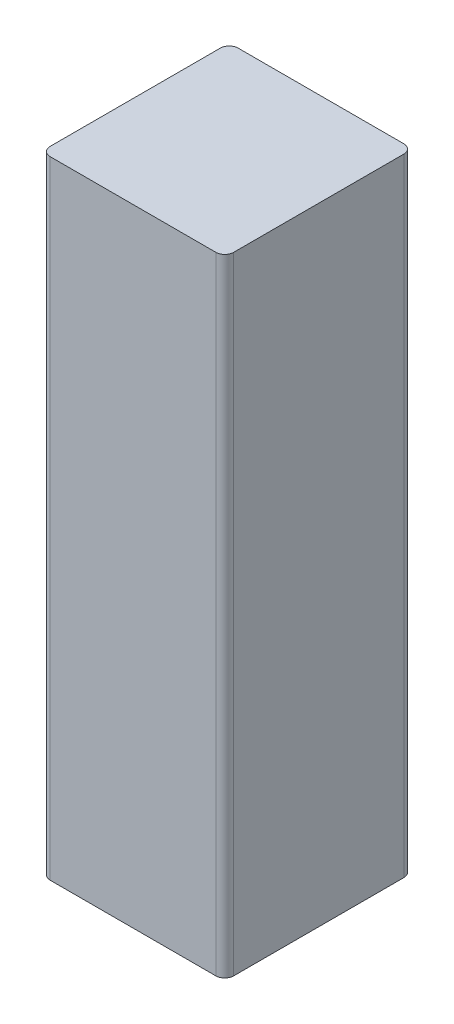
SolidWorks part; units mm, degrees
ref_plane "Front Plane" through (0, 0, 0) normal (0, 0, 1) x (1, 0, 0)
ref_plane "Top Plane" through (0, 0, 0) normal (0, 1, 0) x (1, 0, 0)
ref_plane "Right Plane" through (0, 0, 0) normal (1, 0, 0) x (0, 0, -1)
sketch "Sketch1" plane through (0, 0, 0) normal (0, 1, 0) x (1, 0, 0)
  line L1 (18.5, -21) -> (-18.5, -21)
  line L2 (20.5, -19) -> (20.5, 19)
  line L3 (18.5, 21) -> (-18.5, 21)
  line L4 (-20.5, -19) -> (-20.5, 19)
  line L5 (20.5, -21) -> (-20.5, 21) construction
  line L6 (20.5, 21) -> (-20.5, -21) construction
  arc A0 (-18.5, -21) -> (-20.5, -19) centre (-18.5, -19) cw
  arc A1 (18.5, -21) -> (20.5, -19) centre (18.5, -19) ccw
  arc A2 (20.5, 19) -> (18.5, 21) centre (18.5, 19) ccw
  arc A3 (-18.5, 21) -> (-20.5, 19) centre (-18.5, 19) ccw
  point P0 (0, 0)
  dimension "D3" = 2
  dimension "D1" = 42
  dimension "D2" = 41
extrude "Boss-Extrude1" add sketch "Sketch1" along normal blind 140
